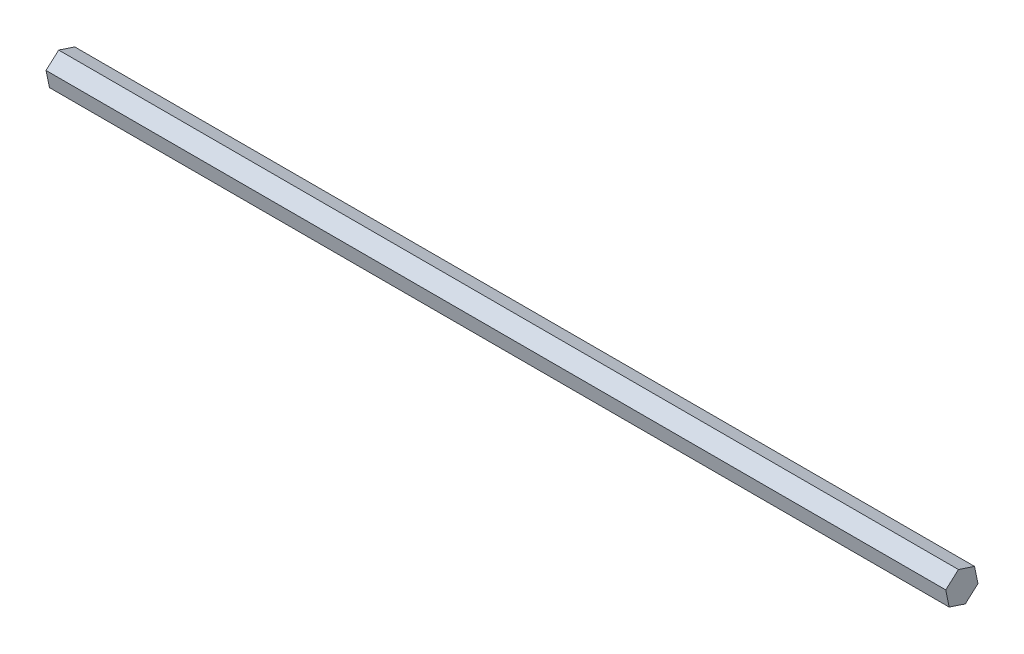
SolidWorks part; units mm, degrees
ref_plane "Front Plane" through (0, 0, 0) normal (0, 0, 1) x (1, 0, 0)
ref_plane "Top Plane" through (0, 0, 0) normal (0, 1, 0) x (1, 0, 0)
ref_plane "Right Plane" through (0, 0, 0) normal (1, 0, 0) x (0, 0, -1)
sketch "Sketch1" plane through (0, 0, 0) normal (1, 0, 0) x (0, 0, -1)
  line L1 (5.474, 4.8783) -> (-1.4877, 7.1798)
  line L2 (-1.4877, 7.1798) -> (-6.9618, 2.3015)
  line L3 (-6.9618, 2.3015) -> (-5.474, -4.8783)
  line L4 (-5.474, -4.8783) -> (1.4877, -7.1798)
  line L5 (1.4877, -7.1798) -> (6.9618, -2.3015)
  line L6 (6.9618, -2.3015) -> (5.474, 4.8783)
  circle A0 centre (0, 0) radius 6.35 construction
  dimension "D1" = 12.7
extrude "Boss-Extrude1" add sketch "Sketch1" along normal blind 388.62
